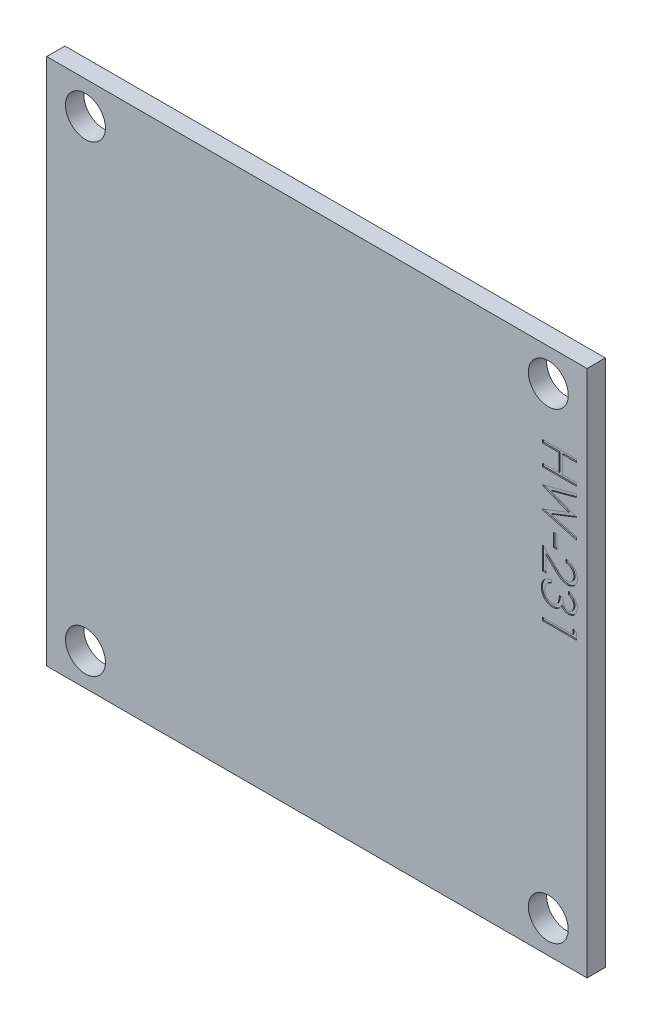
SolidWorks part; units mm, degrees
ref_plane "Front Plane" through (0, 0, 0) normal (0, 0, 1) x (1, 0, 0)
ref_plane "Top Plane" through (0, 0, 0) normal (0, 1, 0) x (1, 0, 0)
ref_plane "Right Plane" through (0, 0, 0) normal (1, 0, 0) x (0, 0, -1)
sketch "Sketch1" plane through (0, 0, 0) normal (0, 0, 1) x (1, 0, 0)
  line L1 (-23.7, -23.15) -> (23.7, -23.15)
  line L2 (-23.7, -23.15) -> (-23.7, 23.15)
  line L3 (-23.7, 23.15) -> (23.7, 23.15)
  line L4 (23.7, -23.15) -> (23.7, 23.15)
  line L5 (-23.7, -23.15) -> (23.7, 23.15) construction
  line L6 (-23.7, 23.15) -> (23.7, -23.15) construction
  point P0 (0, 0)
  dimension "D1" = 46.3
  dimension "D2" = 47.4
extrude "Boss-Extrude1" add sketch "Sketch1" along normal blind 1.6
sketch "Sketch2" plane through (0, 0, 0) normal (0, 0, 1) x (1, 0, 0)
  line L1 (-20.3, -20.3) -> (20.3, -20.3) construction
  line L2 (-20.3, -20.3) -> (-20.3, 20.3) construction
  line L3 (-20.3, 20.3) -> (20.3, 20.3) construction
  line L4 (20.3, -20.3) -> (20.3, 20.3) construction
  line L5 (-20.3, -20.3) -> (20.3, 20.3) construction
  line L6 (-20.3, 20.3) -> (20.3, -20.3) construction
  circle A0 centre (-20.3, 20.3) radius 1.75
  circle A1 centre (20.3, 20.3) radius 1.75
  circle A2 centre (20.3, -20.3) radius 1.75
  circle A3 centre (-20.3, -20.3) radius 1.75
  point P0 (0, 0)
  dimension "D3" = 3.5
  dimension "D1" = 40.6
  dimension "D2" = 40.6
extrude "Cut-Extrude2" cut sketch "Sketch2" along normal through all
sketch "Sketch3" plane through (0, 0, 1.6) normal (0, 0, 1) x (1, 0, 0)
  line L0 (19.77, 16.1986) -> (19.77, 2.153) construction
  text T0 "HW-231" font "Century Gothic" height 3
extrude "Cut-Extrude3" cut sketch "Sketch3" against normal blind 0.1
